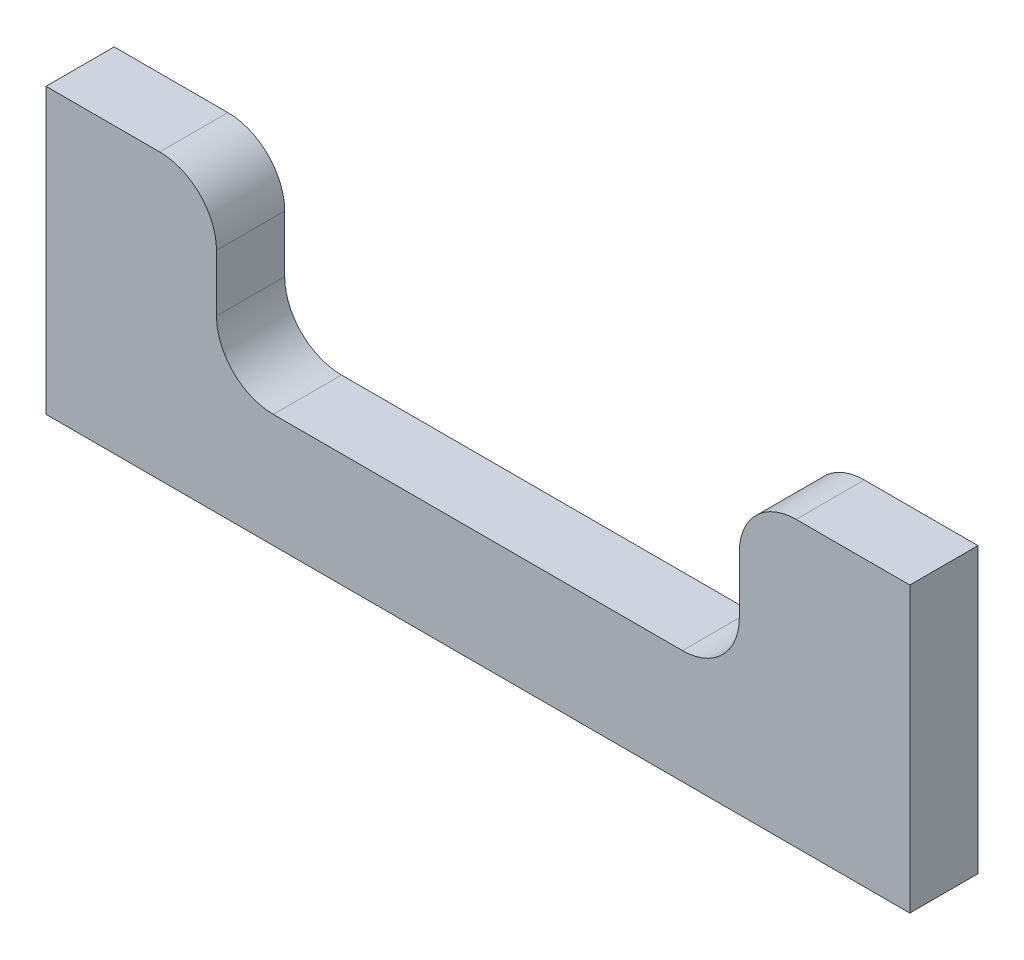
SolidWorks part; units mm, degrees
ref_plane "正面" through (0, 0, 0) normal (0, 0, 1) x (1, 0, 0)
ref_plane "平面" through (0, 0, 0) normal (0, 1, 0) x (1, 0, 0)
ref_plane "右側面" through (0, 0, 0) normal (1, 0, 0) x (0, 0, -1)
sketch "ｽｹｯﾁ1" plane through (0, 0, 0) normal (0, 0, 1) x (1, 0, 0)
  line L0 (0, 0) -> (0, 51.2) construction
  line L1 (-38, 0) -> (38, 0)
  line L2 (38, 0) -> (38, 25)
  line L3 (38, 25) -> (23, 25)
  line L4 (23, 25) -> (23, 10)
  line L5 (23, 10) -> (-23, 10)
  line L6 (-23, 25) -> (-23, 10)
  line L7 (-38, 25) -> (-23, 25)
  line L8 (-38, 0) -> (-38, 25)
  point P9 (0, 10)
  dimension "D1" = 25
  dimension "D2" = 15
  dimension "D3" = 10
  dimension "D4" = 76
extrude "ﾎﾞｽ - 押し出し1" add sketch "ｽｹｯﾁ1" along normal blind 6
fillet "ﾌｨﾚｯﾄ1" radius 5 4 edges at (23, 25, 3) (23, 10, 3) (-23, 10, 3) (-23, 25, 3)
